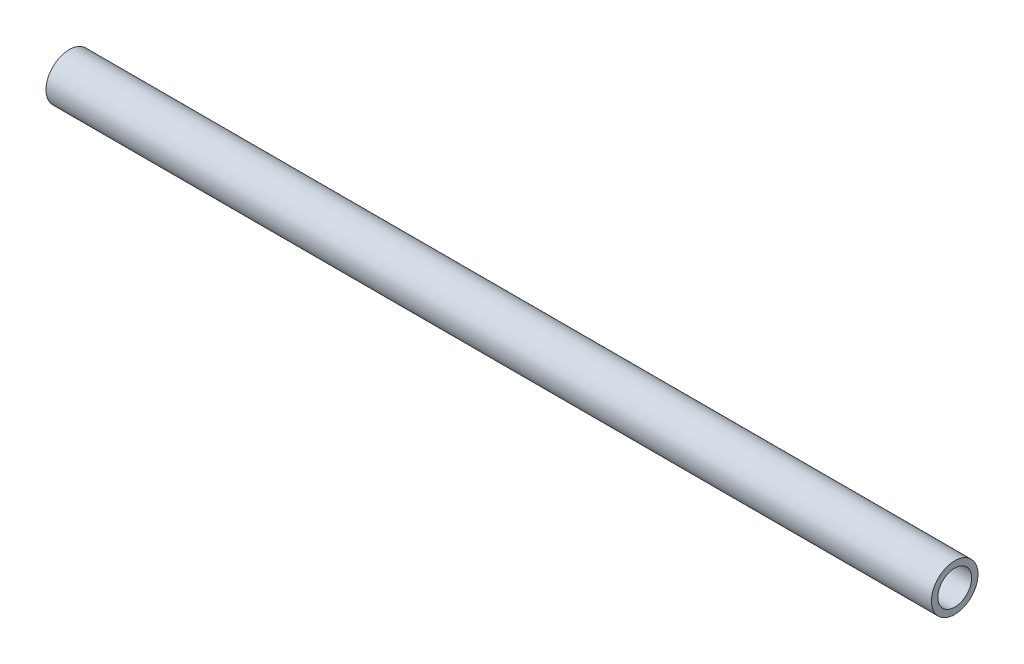
SolidWorks part; units mm, degrees
ref_plane "Front Plane" through (0, 0, 0) normal (0, 0, 1) x (1, 0, 0)
ref_plane "Top Plane" through (0, 0, 0) normal (0, 1, 0) x (1, 0, 0)
ref_plane "Right Plane" through (0, 0, 0) normal (1, 0, 0) x (0, 0, -1)
sketch "Sketch1" plane through (0, 0, 0) normal (1, 0, 0) x (0, 0, -1)
  circle A0 centre (0, 0) radius 13.15
  circle A1 centre (0, 0) radius 9.55
  dimension "D1" = 26.3
  dimension "D2" = 19.1
extrude "Boss-Extrude1" add sketch "Sketch1" along normal blind 500
